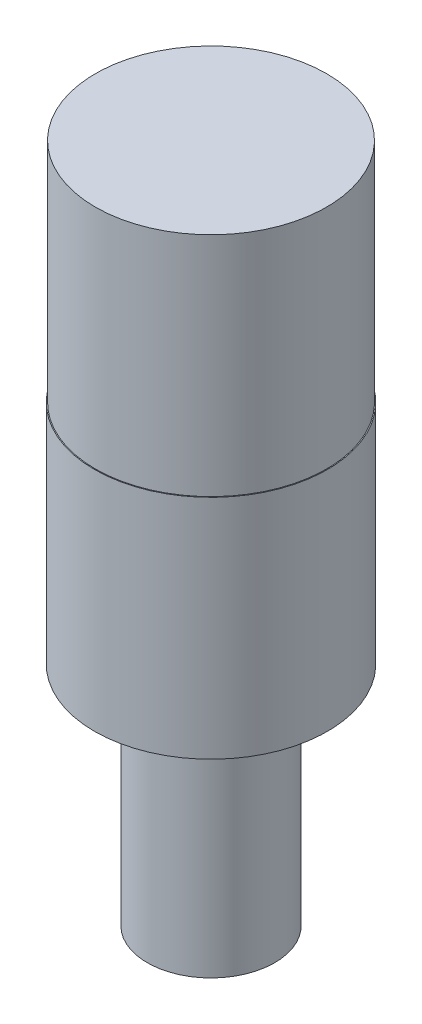
SolidWorks part; units mm, degrees
material "PUR"
ref_plane "Z" through (0, 0, 0) normal (0, 0, 1) x (1, 0, 0)
ref_plane "Y" through (0, 0, 0) normal (0, 1, 0) x (1, 0, 0)
ref_plane "X" through (0, 0, 0) normal (1, 0, 0) x (0, 0, -1)
sketch "Sketch1" plane through (0, 0, 0) normal (0, 1, 0) x (1, 0, 0)
  circle A0 centre (0, 0) radius 7.1438
  dimension "D1" = 14.2875
extrude "Boss-Extrude1" add sketch "Sketch1" along normal blind 38.1
sketch "Sketch2" plane through (0, 38.1, 0) normal (0, 1, 0) x (1, 0, 0)
  circle A0 centre (0, 0) radius 6.475
  circle A1 centre (0, 0) radius 8.5275
  dimension "D1" = 12.95
extrude "Cut-Extrude1" cut sketch "Sketch2" against normal blind 12.7
sketch "Sketch3" plane through (0, 25.4, 0) normal (0, 1, 0) x (1, 0, 0)
  circle A0 centre (0, 0) radius 6.525
  circle A1 centre (0, 0) radius 7.7834
  dimension "D1" = 13.05
extrude "Cut-Extrude2" cut sketch "Sketch3" against normal blind 12.7
sketch "Sketch4" plane through (0, 0, 0) normal (0, -1, 0) x (1, 0, 0)
  circle A0 centre (0, 0) radius 3.5687
  circle A1 centre (0, 0) radius 8.8943
  dimension "D1" = 7.1374
extrude "Cut-Extrude3" cut sketch "Sketch4" against normal blind 12.7
